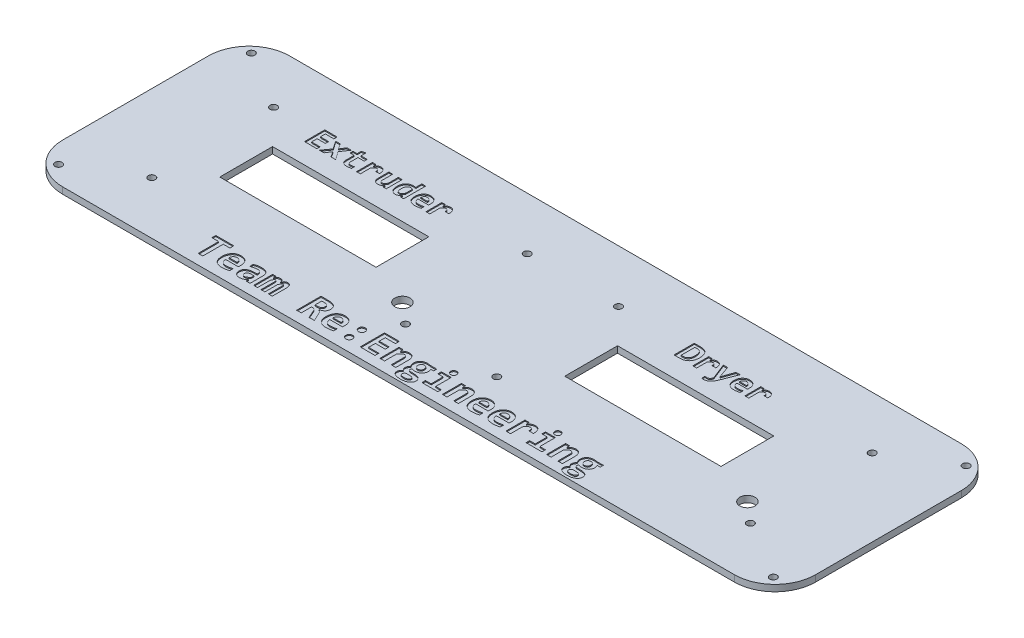
SolidWorks part; units mm, degrees
ref_plane "Front" through (0, 0, 0) normal (0, 0, 1) x (1, 0, 0)
ref_plane "Top" through (0, 0, 0) normal (0, 1, 0) x (1, 0, 0)
ref_plane "Right" through (0, 0, 0) normal (1, 0, 0) x (0, 0, -1)
sketch "Sketch1" plane through (0, 0, 0) normal (0, 1, 0) x (1, 0, 0)
  line L1 (-185.5, 55.9) -> (185.5, 55.9)
  line L2 (-185.5, 55.9) -> (-185.5, -55.9)
  line L3 (-185.5, -55.9) -> (185.5, -55.9)
  line L4 (185.5, 55.9) -> (185.5, -55.9)
  line L5 (-185.5, 55.9) -> (185.5, -55.9) construction
  line L6 (-185.5, -55.9) -> (185.5, 55.9) construction
  point P0 (0, 0)
  dimension "D1" = 111.8
  dimension "D2" = 371
extrude "Boss-Extrude1" add sketch "Sketch1" along normal blind 3.175
fillet "Fillet1" radius 20 4 edges at (-185.5, 1.5875, -55.9) (-185.5, 1.5875, 55.9) (185.5, 1.5875, -55.9) (185.5, 1.5875, 55.9)
sketch "Sketch2" plane through (0, 3.175, 0) normal (0, 1, 0) x (1, 0, 0)
  line L0 (0, 55.9) -> (0, -55.9) construction
  line L1 (165.5, 55.9) -> (-165.5, 55.9) construction
  line L2 (-165.5, -55.9) -> (165.5, -55.9) construction
  line L3 (0, 0) -> (-85, 0) construction
  line L4 (-85, 35) -> (-85, 0) construction
  line L5 (-152.5, -35) -> (-17.5, -35) construction
  line L6 (-152.5, -35) -> (-152.5, 35) construction
  line L7 (-152.5, 35) -> (-17.5, 35) construction
  line L8 (-17.5, -35) -> (-17.5, 35) construction
  line L9 (-152.5, -35) -> (-17.5, 35) construction
  line L10 (-152.5, 35) -> (-17.5, -35) construction
  line L11 (-85, 0) -> (-152.5, 0) construction
  line L12 (152.5, -35) -> (152.5, 35) construction
  line L13 (-131, -13) -> (-54, -13)
  line L14 (-131, -13) -> (-131, 13)
  line L15 (-131, 13) -> (-54, 13)
  line L16 (-54, -13) -> (-54, 13)
  line L17 (-131, -13) -> (-54, 13) construction
  line L18 (-131, 13) -> (-54, -13) construction
  line L19 (152.5, -35) -> (17.5, -35) construction
  line L20 (17.5, -35) -> (17.5, 35) construction
  line L21 (152.5, 35) -> (17.5, 35) construction
  line L23 (39, 13) -> (116, 13)
  line L24 (39, 13) -> (39, -13)
  line L25 (39, -13) -> (116, -13)
  line L26 (116, 13) -> (116, -13)
  line L27 (39, 13) -> (116, -13) construction
  line L28 (39, -13) -> (116, 13) construction
  circle A0 centre (-147.5, 30) radius 1.75
  circle A1 centre (-147.5, -30) radius 1.75
  circle A2 centre (-22.5, -30) radius 1.75
  circle A3 centre (-22.5, 30) radius 1.75
  circle A4 centre (147.5, 30) radius 1.75
  circle A5 centre (147.5, -30) radius 1.75
  circle A6 centre (22.5, -30) radius 1.75
  circle A7 centre (22.5, 30) radius 1.75
  point P31 (-92.5, 0)
  point P40 (77.5, 0)
  dimension "D4" = 3.5
  dimension "D5" = 5
  dimension "D6" = 5
  dimension "D1" = 135
  dimension "D2" = 70
  dimension "D3" = 85
  dimension "D7" = 60
  dimension "D8" = 35
  dimension "D9" = 26
  dimension "D10" = 77
  dimension "D11" = 60
  dimension "D12" = 35
  dimension "D13" = 26
  dimension "D14" = 77
extrude "Cut-Extrude1" cut sketch "Sketch2" against normal up to next
sketch "Sketch6" plane through (0, 3.175, 0) normal (0, 1, 0) x (1, 0, 0)
  circle A0 centre (176.1066, -47.3372) radius 2.5 construction
  circle A1 centre (176.1066, -47.3372) radius 2.5 construction
  circle A2 centre (-176.1066, -47.3372) radius 2.5 construction
  circle A3 centre (-176.1066, -47.3372) radius 2.5 construction
  circle A4 centre (-176.1066, 47.6638) radius 2.5 construction
  circle A5 centre (-176.1066, 47.6638) radius 2.5 construction
  circle A6 centre (176.1066, 47.6638) radius 2.5 construction
  circle A7 centre (176.1066, 47.6638) radius 2.5 construction
  circle A8 centre (176.1066, 47.6638) radius 1.75
  circle A9 centre (-176.1066, 47.6638) radius 1.75
  circle A10 centre (-176.1066, -47.3372) radius 1.75
  circle A11 centre (176.1066, -47.3372) radius 1.75
  dimension "D1" = 3.5
extrude "Cut-Extrude2" cut sketch "Sketch6" against normal up to next
sketch "Sketch7" plane through (0, 3.175, 0) normal (0, 1, 0) x (1, 0, 0)
  line L0 (185.5, -21.5) -> (137.5, -21.5) construction
  line L1 (185.5, -35.9) -> (185.5, 35.9) construction
  line L2 (137.5, -21.5) -> (-32.5, -21.5) construction
  line L3 (-32.5, -21.5) -> (-185.5, -21.5) construction
  line L4 (-185.5, 35.9) -> (-185.5, -35.9) construction
  circle A0 centre (-32.5, -21.5) radius 3.75
  circle A1 centre (137.5, -21.5) radius 3.75
  circle A2 centre (-22.5, -30) radius 1.75 construction
  circle A3 centre (147.5, -30) radius 1.75 construction
  dimension "D1" = 10
  dimension "D2" = 10
  dimension "D3" = 8.5
  dimension "D4" = 7.5
extrude "Cut-Extrude3" cut sketch "Sketch7" against normal up to next
sketch "Sketch11" plane through (0, 3.175, 0) normal (0, 1, 0) x (1, 0, 0)
  line L5 (-54, 23) -> (-131, 23)
  line L6 (-54, 23) -> (-131, 23) construction
  line L8 (116, 23) -> (39, 23)
  line L9 (116, 23) -> (39, 23) construction
  text T0 "Extruder" font "Consolas" height 10
  text T1 "Dryer" font "Consolas" height 10
  dimension "D1" = 10
  dimension "D2" = 10
extrude "Cut-Extrude4" cut sketch "Sketch11" against normal blind 0.5
sketch "Sketch12" plane through (0, 3.175, 0) normal (0, 1, 0) x (1, 0, 0)
  line L2 (-165.5, -50.9) -> (165.5, -50.9)
  line L3 (-165.5, -50.9) -> (165.5, -50.9) construction
  text T0 "Team Re:Engineering  " font "Consolas" height 12
  dimension "D1" = 5
extrude "Cut-Extrude5" cut sketch "Sketch12" against normal blind 0.5
